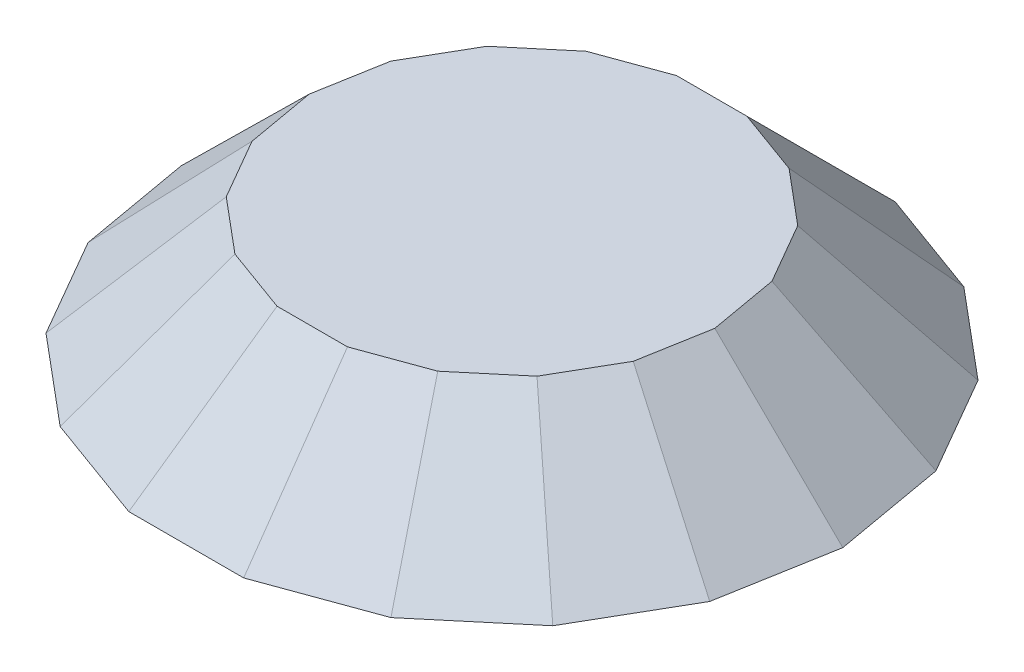
SolidWorks part; units mm, degrees
ref_plane "Front Plane" through (0, 0, 0) normal (0, 0, 1) x (1, 0, 0)
ref_plane "Top Plane" through (0, 0, 0) normal (0, 1, 0) x (1, 0, 0)
ref_plane "Right Plane" through (0, 0, 0) normal (1, 0, 0) x (0, 0, -1)
sketch "Sketch1" plane through (0, 0, 0) normal (0, 1, 0) x (1, 0, 0)
  line L1 (105, 0) -> (98.6677, 35.9121)
  line L2 (98.6677, 35.9121) -> (80.4347, 67.4927)
  line L3 (80.4347, 67.4927) -> (52.5, 90.9327)
  line L4 (52.5, 90.9327) -> (18.2331, 103.4048)
  line L5 (18.2331, 103.4048) -> (-18.2331, 103.4048)
  line L6 (-18.2331, 103.4048) -> (-52.5, 90.9327)
  line L7 (-52.5, 90.9327) -> (-80.4347, 67.4927)
  line L8 (-80.4347, 67.4927) -> (-98.6677, 35.9121)
  line L9 (-98.6677, 35.9121) -> (-105, 0)
  line L10 (-105, 0) -> (-98.6677, -35.9121)
  line L11 (-98.6677, -35.9121) -> (-80.4347, -67.4927)
  line L12 (-80.4347, -67.4927) -> (-52.5, -90.9327)
  line L13 (-52.5, -90.9327) -> (-18.2331, -103.4048)
  line L14 (-18.2331, -103.4048) -> (18.2331, -103.4048)
  line L15 (18.2331, -103.4048) -> (52.5, -90.9327)
  line L16 (52.5, -90.9327) -> (80.4347, -67.4927)
  line L17 (80.4347, -67.4927) -> (98.6677, -35.9121)
  line L18 (98.6677, -35.9121) -> (105, 0)
  circle A0 centre (0, 0) radius 103.4048 construction
  dimension "D1" = 210
extrude "Boss-Extrude2" add sketch "Sketch1" along normal blind 40 draft 45
shell "Shell1" thickness 2
